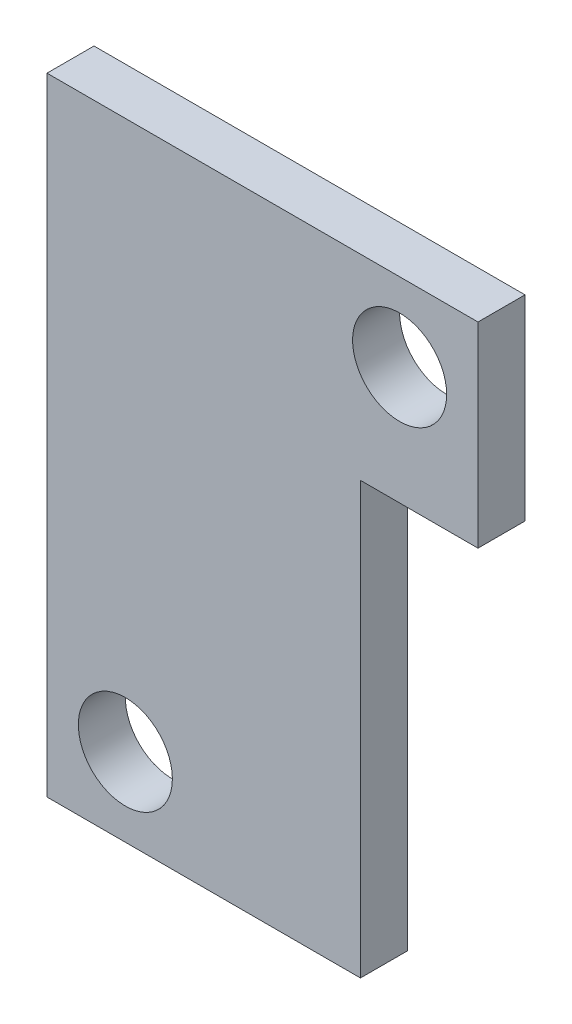
SolidWorks part; units mm, degrees
ref_plane "Front Plane" through (0, 0, 0) normal (0, 0, 1) x (1, 0, 0)
ref_plane "Top Plane" through (0, 0, 0) normal (0, 1, 0) x (1, 0, 0)
ref_plane "Right Plane" through (0, 0, 0) normal (1, 0, 0) x (0, 0, -1)
sketch "Sketch1" plane through (0, 0, 0) normal (0, 0, 1) x (1, 0, 0)
  line L0 (8, 0) -> (8, 11)
  line L1 (0, 0) -> (8, 0)
  line L2 (0, 0) -> (0, 16)
  line L3 (0, 16) -> (11, 16)
  line L4 (11, 11) -> (11, 16)
  line L5 (8, 11) -> (11, 11)
  circle A0 centre (9, 14) radius 1.2
  circle A1 centre (2, 2) radius 1.2
  dimension "D3" = 2.4
  dimension "D1" = 16
  dimension "D2" = 11
  dimension "D4" = 2
  dimension "D5" = 2
  dimension "D6" = 2
  dimension "D7" = 2
  dimension "D8" = 3
  dimension "D9" = 11
extrude "Boss-Extrude1" add sketch "Sketch1" along normal blind 1.2
equation "\"BoardLength\" = 11"
equation "\"BoardHeight\"= 16"
equation "\"ScrewHoleDiameter\"= 2.4"
equation "\"BoardThickness\" = 0.4"
equation "\"D1@Sketch1\"=\"BoardHeight\""
equation "\"D2@Sketch1\"=\"BoardLength\""
equation "\"D3@Sketch1\"=\"ScrewHoleDiameter\""
equation "\"PrintThickness\"= 1.2"
equation "\"D1@Boss-Extrude1\"=\"PrintThickness\""
